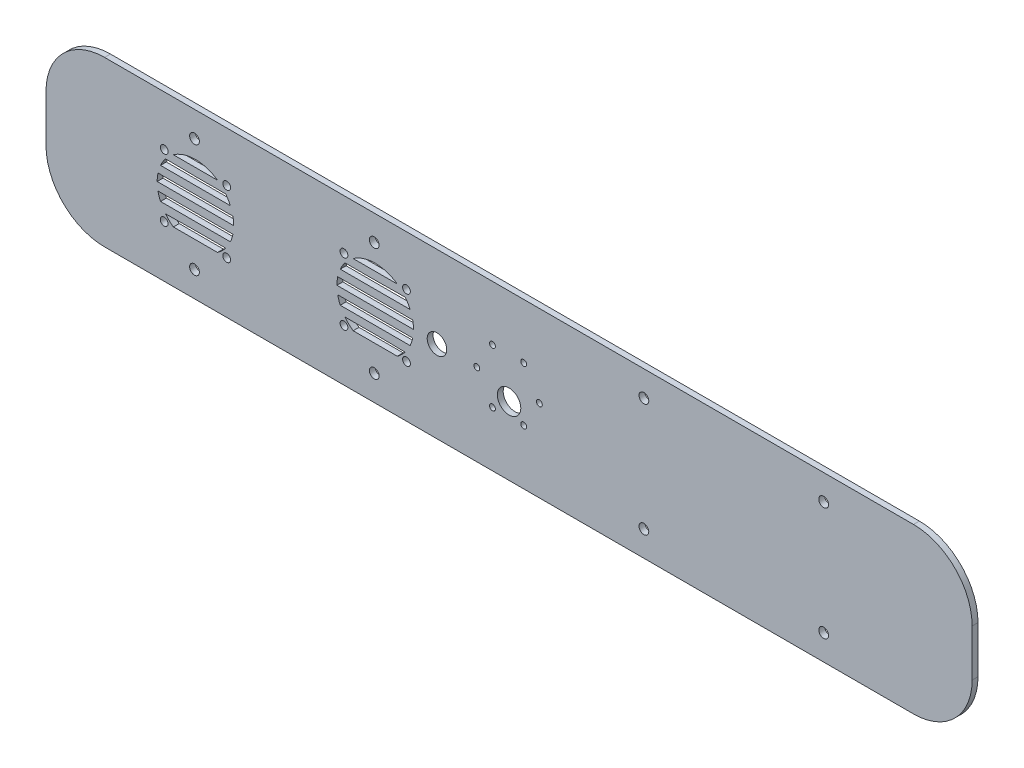
SolidWorks part; units mm, degrees
ref_plane "Alzado" through (0, 0, 0) normal (0, 0, 1) x (1, 0, 0)
ref_plane "Planta" through (0, 0, 0) normal (0, 1, 0) x (1, 0, 0)
ref_plane "Vista lateral" through (0, 0, 0) normal (1, 0, 0) x (0, 0, -1)
sketch "Croquis1" plane through (0, 0, 0) normal (0, 0, 1) x (1, 0, 0)
  line L0 (207, -38) -> (-207, -38)
  line L1 (237, -8) -> (237, 16)
  line L2 (207, 46) -> (-207, 46)
  line L3 (-237, -8) -> (-237, 16)
  line L4 (237, -38) -> (-237, 46) construction
  line L5 (237, 46) -> (-237, -38) construction
  line L6 (0, 4) -> (-24.9, 4) construction
  line L7 (0, 4) -> (15.5, 4) construction
  line L8 (0, 4) -> (0, -3) construction
  arc A0 (-237, 16) -> (-207, 46) centre (-207, 16) cw
  arc A1 (207, -38) -> (237, -8) centre (207, -8) ccw
  arc A2 (207, 46) -> (237, 16) centre (207, 16) cw
  arc A3 (-237, -8) -> (-207, -38) centre (-207, -8) ccw
  circle A22 centre (15.5, 4) radius 1.5
  circle A24 centre (7.4961, -9.8632) radius 1.5
  circle A25 centre (-8.5117, -9.8632) radius 1.5
  circle A26 centre (-16.5156, 4) radius 1.5
  circle A27 centre (-8.5117, 17.8632) radius 1.5
  circle A28 centre (7.4961, 17.8632) radius 1.5
  circle A30 centre (0, -3) radius 6
  point P0 (0, 4)
  dimension "D2" = 30
  dimension "D3" = 30
  dimension "D5" = 15.5
  dimension "D7" = 6
  dimension "D6" = 3
  dimension "D1" = 474
  dimension "D4" = 24.9
  dimension "D8" = 84
  dimension "D10" = 7
extrude "Saliente-Extruir1" add sketch "Croquis1" along normal blind 3
sketch "Croquis3" plane through (0, 0, 3) normal (0, 0, 1) x (1, 0, 0)
  line L0 (-176.5101, 22.4584) -> (-176.5101, 20.4584) construction
  line L1 (207, 46) -> (-207, 46) construction
  line L2 (-207, 46) -> (-177, 46) construction
  line L3 (-144.5101, 20.4584) -> (-142.5101, 20.4584) construction
  line L6 (-171.8135, -11.5416) -> (-149.2066, -11.5416)
  line L13 (-160.5101, 8.4584) -> (-141.3328, 8.4584)
  line L14 (-180.1001, 4.4584) -> (-140.9201, 4.4584)
  line L21 (-160.5101, 8.4584) -> (-179.6874, 8.4584)
  line L22 (-160.5101, 12.4584) -> (-142.628, 12.4584)
  line L23 (-160.5101, 12.4584) -> (-178.3921, 12.4584)
  line L24 (-160.5101, 16.4584) -> (-145.0256, 16.4584)
  line L25 (-160.5101, 16.4584) -> (-175.8506, 16.6419)
  line L26 (-160.5101, 0.4584) -> (-141.3328, 0.4584)
  line L27 (-160.5101, 0.4584) -> (-179.6874, 0.4584)
  line L28 (-160.5101, -3.5416) -> (-142.628, -3.5416)
  line L29 (-160.5101, -3.5416) -> (-178.3921, -3.5416)
  line L30 (-160.5101, -7.5416) -> (-145.0256, -7.5416)
  line L31 (-160.5101, -7.5416) -> (-175.8506, -7.7251)
  line L32 (-171.8135, 20.4584) -> (-149.2066, 20.4584)
  line L37 (-57.2066, 20.4584) -> (-79.8135, 20.4584)
  line L38 (-68.5101, -7.5416) -> (-53.1696, -7.7251)
  line L39 (-68.5101, -7.5416) -> (-83.9945, -7.5416)
  line L40 (-68.5101, -3.5416) -> (-50.628, -3.5416)
  line L41 (-68.5101, -3.5416) -> (-86.3921, -3.5416)
  line L42 (-68.5101, 0.4584) -> (-49.3328, 0.4584)
  line L43 (-68.5101, 0.4584) -> (-87.6874, 0.4584)
  line L44 (-68.5101, 16.4584) -> (-53.1696, 16.6419)
  line L45 (-68.5101, 16.4584) -> (-83.9945, 16.4584)
  line L46 (-68.5101, 12.4584) -> (-50.628, 12.4584)
  line L47 (-68.5101, 12.4584) -> (-86.3921, 12.4584)
  line L48 (-68.5101, 8.4584) -> (-49.3328, 8.4584)
  line L49 (-48.9201, 4.4584) -> (-88.1001, 4.4584)
  line L50 (-68.5101, 8.4584) -> (-87.6874, 8.4584)
  line L51 (-57.2066, -11.5416) -> (-79.8135, -11.5416)
  line L52 (-86.5101, 20.4584) -> (-84.5101, 20.4584) construction
  circle A0 centre (-176.5101, 20.4584) radius 2
  circle A1 centre (-144.5101, 20.4584) radius 2
  circle A2 centre (-176.5101, -11.5416) radius 2
  circle A3 centre (-144.5101, -11.5416) radius 2
  arc A9 (-175.8506, 16.6419) -> (-178.3921, 12.4584) centre (-160.5101, 4.4584) ccw
  arc A10 (-149.2066, 20.4584) -> (-171.8135, 20.4584) centre (-160.5101, 4.4584) ccw
  arc A11 (-142.628, 12.4584) -> (-145.0256, 16.4584) centre (-160.5101, 4.4584) ccw
  arc A12 (-179.6874, 8.4584) -> (-180.1001, 4.4584) centre (-160.5101, 4.4584) ccw
  arc A13 (-179.6874, 0.4584) -> (-178.3921, -3.5416) centre (-160.5101, 4.4584) ccw
  arc A14 (-140.9201, 4.4584) -> (-141.3328, 8.4584) centre (-160.5101, 4.4584) ccw
  arc A15 (-142.628, -3.5416) -> (-141.3328, 0.4584) centre (-160.5101, 4.4584) ccw
  arc A16 (-175.8506, -7.7251) -> (-171.8135, -11.5416) centre (-160.5101, 4.4584) ccw
  arc A17 (-149.2066, -11.5416) -> (-145.0256, -7.5416) centre (-160.5101, 4.4584) ccw
  arc A18 (-79.8135, -11.5416) -> (-83.9945, -7.5416) centre (-68.5101, 4.4584) cw
  arc A19 (-53.1696, -7.7251) -> (-57.2066, -11.5416) centre (-68.5101, 4.4584) cw
  arc A20 (-86.3921, -3.5416) -> (-87.6874, 0.4584) centre (-68.5101, 4.4584) cw
  arc A21 (-88.1001, 4.4584) -> (-87.6874, 8.4584) centre (-68.5101, 4.4584) cw
  arc A22 (-49.3328, 0.4584) -> (-50.628, -3.5416) centre (-68.5101, 4.4584) cw
  arc A23 (-49.3328, 8.4584) -> (-48.9201, 4.4584) centre (-68.5101, 4.4584) cw
  arc A24 (-86.3921, 12.4584) -> (-83.9945, 16.4584) centre (-68.5101, 4.4584) cw
  arc A25 (-79.8135, 20.4584) -> (-57.2066, 20.4584) centre (-68.5101, 4.4584) cw
  arc A26 (-53.1696, 16.6419) -> (-50.628, 12.4584) centre (-68.5101, 4.4584) cw
  circle A27 centre (-84.5101, -11.5416) radius 2
  circle A28 centre (-52.5101, -11.5416) radius 2
  circle A29 centre (-84.5101, 20.4584) radius 2
  circle A30 centre (-52.5101, 20.4584) radius 2
  dimension "D5" = 4
  dimension "D6" = 4
  dimension "D7" = 4
  dimension "D8" = 4
  dimension "D15" = 39.18
  dimension "D2" = 30
  dimension "D3" = 32
  dimension "D4" = 32
  dimension "D14" = 60
  dimension "D17" = 4
  dimension "D18" = 4
  dimension "D19" = 4
extrude "Cortar-Extruir1" cut sketch "Croquis3" against normal blind 10
sketch "Croquis4" plane through (0, 0, 3) normal (0, 0, 1) x (1, 0, 0)
  circle A0 centre (-36.9, 4) radius 5
  dimension "D2" = 10
extrude "Cortar-Extruir2" cut sketch "Croquis4" against normal blind 5
sketch "Croquis5" plane through (0, 0, 0) normal (0, 0, -1) x (-1, 0, 0)
  line L0 (161, 33) -> (161, 46) construction
  line L1 (-207, 46) -> (207, 46) construction
  line L2 (69, -25) -> (69, -38) construction
  line L3 (161, -25) -> (161, -38) construction
  line L4 (-161, -25) -> (-161, -38) construction
  line L7 (69, 33) -> (69, 46) construction
  line L8 (-69, -25) -> (-69, -38) construction
  line L9 (-69, 33) -> (-69, 46) construction
  line L10 (-161, 33) -> (-161, 46) construction
  circle A0 centre (69, 33) radius 2.5
  circle A1 centre (161, 33) radius 2.5
  circle A2 centre (161, -25) radius 2.5
  circle A3 centre (69, -25) radius 2.5
  circle A4 centre (-69, -25) radius 2.5
  circle A5 centre (-161, -25) radius 2.5
  circle A6 centre (-161, 33) radius 2.5
  circle A7 centre (-69, 33) radius 2.5
  dimension "D2" = 5
  dimension "D4" = 5
  dimension "D1" = 13
  dimension "D3" = 13
extrude "Cortar-Extruir3" cut sketch "Croquis5" against normal blind 10
